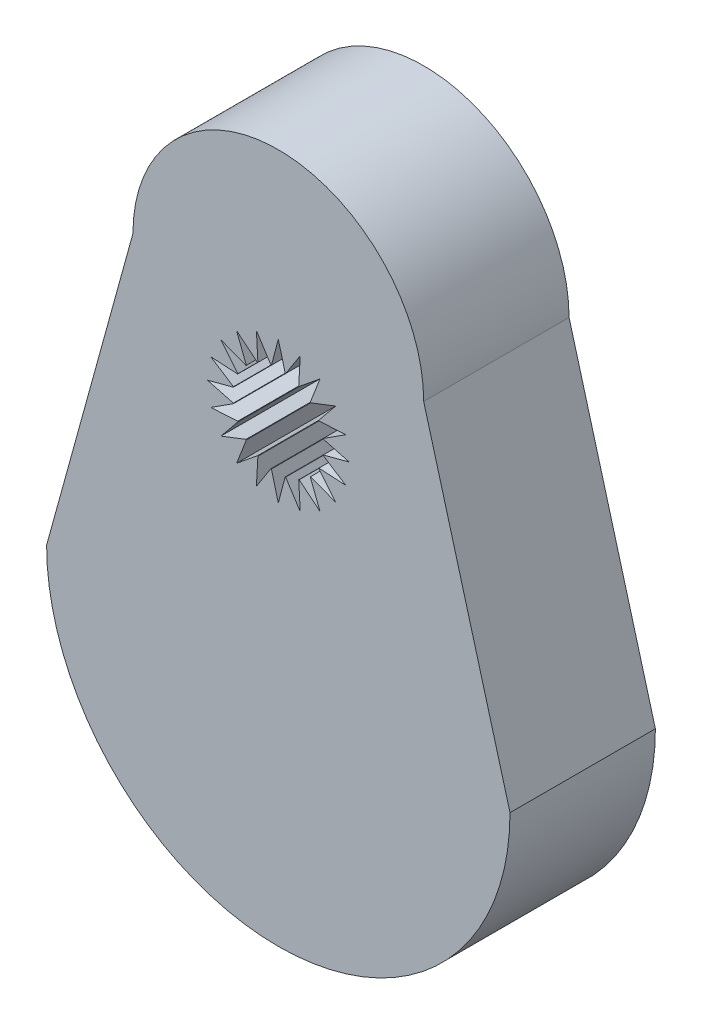
SolidWorks part; units mm, degrees
ref_plane "前视基准面" through (0, 0, 0) normal (0, 0, 1) x (1, 0, 0)
ref_plane "上视基准面" through (0, 0, 0) normal (0, 1, 0) x (1, 0, 0)
ref_plane "右视基准面" through (0, 0, 0) normal (1, 0, 0) x (0, 0, -1)
sketch "草图1" plane through (0, 0, 0) normal (0, 0, 1) x (1, 0, 0)
  line L0 (0, 55.1947) -> (0, -54.9322) construction
  line L5 (-10, 24.7911) -> (-15.9377, 3.2624)
  line L6 (10, 24.7911) -> (15.9377, 3.2624)
  arc A0 (10, 24.7911) -> (-10, 24.7911) centre (0, 24.7911) ccw
  arc A1 (-15.9377, 3.2624) -> (15.9377, 3.2624) centre (0, 3.2624) ccw
extrude "凸台-拉伸1" add sketch "草图1" against normal blind 10
sketch "草图3" plane through (0, 0, 0) normal (0, 0, 1) x (1, 0, 0)
  line L0 (0, 0) -> (0, 13.7409) construction
  line L1 (0, 23.501) -> (-0.4724, 21.7117)
  line L2 (-0.4724, 21.7117) -> (0, 23.501)
  line L3 (0, 15.4943) -> (0, 37.2419) construction
  line L4 (0.4724, 21.7117) -> (0, 23.501)
  line L5 (1.508, 23.2622) -> (0.5058, 21.7064)
  line L6 (1.4044, 21.4144) -> (1.508, 23.2622)
  line L7 (2.8684, 22.569) -> (1.4345, 21.3991)
  line L8 (2.1989, 20.8437) -> (2.8684, 22.569)
  line L9 (3.9481, 21.4894) -> (2.2228, 20.8198)
  line L10 (2.7781, 20.0554) -> (3.9481, 21.4894)
  line L11 (4.6412, 20.129) -> (2.7935, 20.0253)
  line L12 (3.0854, 19.1268) -> (4.6412, 20.129)
  line L13 (4.8801, 18.621) -> (3.0907, 19.0934)
  line L14 (3.0907, 18.1486) -> (4.8801, 18.621)
  line L15 (4.6412, 17.1129) -> (3.0854, 18.1152)
  line L16 (2.7935, 17.2166) -> (4.6412, 17.1129)
  line L17 (3.9481, 15.7525) -> (2.7781, 17.1865)
  line L18 (2.2228, 16.4221) -> (3.9481, 15.7525)
  line L19 (2.8684, 14.6729) -> (2.1989, 16.3982)
  line L20 (1.4345, 15.8428) -> (2.8684, 14.6729)
  line L21 (1.508, 13.9797) -> (1.4044, 15.8275)
  line L22 (0.5058, 15.5355) -> (1.508, 13.9797)
  line L23 (0, 13.7409) -> (0.4724, 15.5302)
  line L24 (-0.4724, 15.5302) -> (0, 13.7409)
  line L25 (-1.508, 13.9797) -> (-0.5058, 15.5355)
  line L26 (-1.4044, 15.8275) -> (-1.508, 13.9797)
  line L27 (-2.8684, 14.6729) -> (-1.4345, 15.8428)
  line L28 (-2.1989, 16.3982) -> (-2.8684, 14.6729)
  line L29 (-3.9481, 15.7525) -> (-2.2228, 16.4221)
  line L30 (-2.7781, 17.1865) -> (-3.9481, 15.7525)
  line L31 (-4.6412, 17.1129) -> (-2.7935, 17.2166)
  line L32 (-3.0854, 18.1152) -> (-4.6412, 17.1129)
  line L33 (-4.8801, 18.621) -> (-3.0907, 18.1486)
  line L34 (-3.0907, 19.0934) -> (-4.8801, 18.621)
  line L35 (-4.6412, 20.129) -> (-3.0854, 19.1268)
  line L36 (-2.7935, 20.0253) -> (-4.6412, 20.129)
  line L37 (-3.9481, 21.4894) -> (-2.7781, 20.0554)
  line L38 (-2.2228, 20.8198) -> (-3.9481, 21.4894)
  line L39 (-2.8684, 22.569) -> (-2.1989, 20.8437)
  line L40 (-1.4345, 21.3991) -> (-2.8684, 22.569)
  line L41 (-1.508, 23.2622) -> (-1.4044, 21.4144)
  line L42 (-0.5058, 21.7064) -> (-1.508, 23.2622)
  circle A0 centre (0, 18.621) radius 4.8801
  arc A1 (-2.1989, 20.8437) -> (-2.2228, 20.8198) centre (0, 18.621) ccw
  arc A2 (-1.4044, 21.4144) -> (-1.4345, 21.3991) centre (0, 18.621) ccw
  arc A3 (-0.4724, 21.7117) -> (-0.5058, 21.7064) centre (0, 18.621) ccw
  arc A4 (0.5058, 21.7064) -> (0.4724, 21.7117) centre (0, 18.621) ccw
  arc A5 (1.4345, 21.3991) -> (1.4044, 21.4144) centre (0, 18.621) ccw
  arc A6 (2.2228, 20.8198) -> (2.1989, 20.8437) centre (0, 18.621) ccw
  arc A7 (2.7935, 20.0253) -> (2.7781, 20.0554) centre (0, 18.621) ccw
  arc A8 (3.0907, 19.0934) -> (3.0854, 19.1268) centre (0, 18.621) ccw
  arc A9 (3.0854, 18.1152) -> (3.0907, 18.1486) centre (0, 18.621) ccw
  arc A10 (2.7781, 17.1865) -> (2.7935, 17.2166) centre (0, 18.621) ccw
  arc A11 (2.1989, 16.3982) -> (2.2228, 16.4221) centre (0, 18.621) ccw
  arc A12 (1.4044, 15.8275) -> (1.4345, 15.8428) centre (0, 18.621) ccw
  arc A13 (0.4724, 15.5302) -> (0.5058, 15.5355) centre (0, 18.621) ccw
  arc A14 (-0.5058, 15.5355) -> (-0.4724, 15.5302) centre (0, 18.621) ccw
  arc A15 (-1.4345, 15.8428) -> (-1.4044, 15.8275) centre (0, 18.621) ccw
  arc A16 (-2.2228, 16.4221) -> (-2.1989, 16.3982) centre (0, 18.621) ccw
  arc A17 (-2.7935, 17.2166) -> (-2.7781, 17.1865) centre (0, 18.621) ccw
  arc A18 (-3.0907, 18.1486) -> (-3.0854, 18.1152) centre (0, 18.621) ccw
  arc A19 (-3.0854, 19.1268) -> (-3.0907, 19.0934) centre (0, 18.621) ccw
  arc A20 (-2.7781, 20.0554) -> (-2.7935, 20.0253) centre (0, 18.621) ccw
  dimension "D1" = 20
extrude "切除-拉伸2" cut sketch "草图3" against normal blind 8 contours L37 A20 L36 L35 A19 L34 L33 A18 L32 L31 A17 L30 L29 A16 L28 L27 A15 L26 L25 A14 L24 L23 A13 L22 L21 A12 L20 L19 A11 L18 L17 A10 L16 L15 A9 L14 L13 A8 L12 L11 A7 L10 L9 A6 L8 L7 A5 L6 L5 A4 L4
